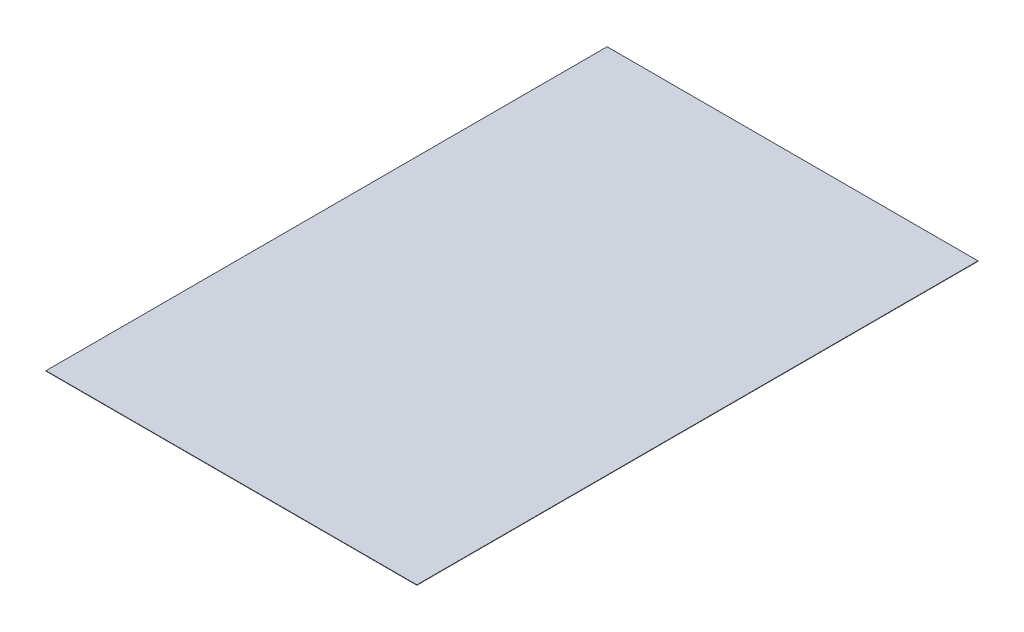
SolidWorks part; units mm, degrees
ref_plane "Front Plane" through (0, 0, 0) normal (0, 0, 1) x (1, 0, 0)
ref_plane "Top Plane" through (0, 0, 0) normal (0, 1, 0) x (1, 0, 0)
ref_plane "Right Plane" through (0, 0, 0) normal (1, 0, 0) x (0, 0, -1)
sketch "Sketch1" plane through (0, 0, 0) normal (0, 0, 1) x (1, 0, 0)
  line L0 (-152.4, 0) -> (152.4, 0) construction
  line L1 (0, -0.1016) -> (0, 0.1016) construction
  point P5 (0, 0)
  point P9 (0, 0)
  dimension "Width" = 304.8
  dimension "Wire Diameter" = 0.2032
sketch "Sketch2" plane through (0, 0, 0) normal (1, 0, 0) x (0, 0, -1)
  line L0 (-152.4, 0) -> (152.4, 0) construction
  point P3 (0, 0)
  dimension "Length" = 304.8
sketch "Sketch3" plane through (0, 0, 0) normal (0, 0, 1) x (1, 0, 0)
  line L1 (-152.4, -0.1016) -> (152.4, -0.1016)
  line L2 (-152.4, -0.1016) -> (-152.4, 0.1016)
  line L3 (-152.4, 0.1016) -> (152.4, 0.1016)
  line L4 (152.4, -0.1016) -> (152.4, 0.1016)
  line L5 (-152.4, -0.1016) -> (152.4, 0.1016) construction
  line L6 (-152.4, 0.1016) -> (152.4, -0.1016) construction
  point P0 (0, 0)
extrude "Boss-Extrude1" add sketch "Sketch3" along normal mid plane 304.8
sketch "Sketch4" plane through (0, 0.1016, 0) normal (0, 1, 0) x (1, 0, 0)
  line L0 (152.4, 152.4) -> (-152.4, 152.4) construction
  line L1 (152.4, -152.4) -> (152.4, 152.4) construction
  line L2 (152.4, -152.4) -> (-152.4, -152.4) construction
  line L3 (-152.4, -152.4) -> (-152.4, 152.4) construction
  point P0 (-151.638, 0)
  point P1 (0, 151.638)
  point P2 (151.638, 0)
  point P3 (0, -151.638)
  dimension "D1" = 0.762
  dimension "D2" = 0.762
  dimension "D3" = 0.762
  dimension "D4" = 0.762
sketch "Sketch5" plane through (0, 0, 0) normal (0, 1, 0) x (1, 0, 0)
  line L2 (-152.4, 152.4) -> (-152.4, 147.32)
  line L3 (-152.4, 147.32) -> (45.72, 147.32)
  line L5 (152.4, -152.4) -> (-152.4, -152.4) construction
  line L8 (152.4, -152.4) -> (45.72, -152.4)
  line L9 (45.72, 147.32) -> (45.72, -152.4)
  line L10 (152.4, 152.4) -> (152.4, -152.4)
  line L11 (152.4, -152.4) -> (152.4, 152.4) construction
  line L12 (-152.4, 152.4) -> (152.4, 152.4)
  dimension "D1" = 5.08
  dimension "D2" = 106.68
extrude "Cut-Extrude1" cut sketch "Sketch5" against normal through all both and the other way through all
equation "\"D1@Boss-Extrude1\"=\"Length@Sketch2\""
equation "\"D2@Sketch4\"=\"D1@Sketch4\""
